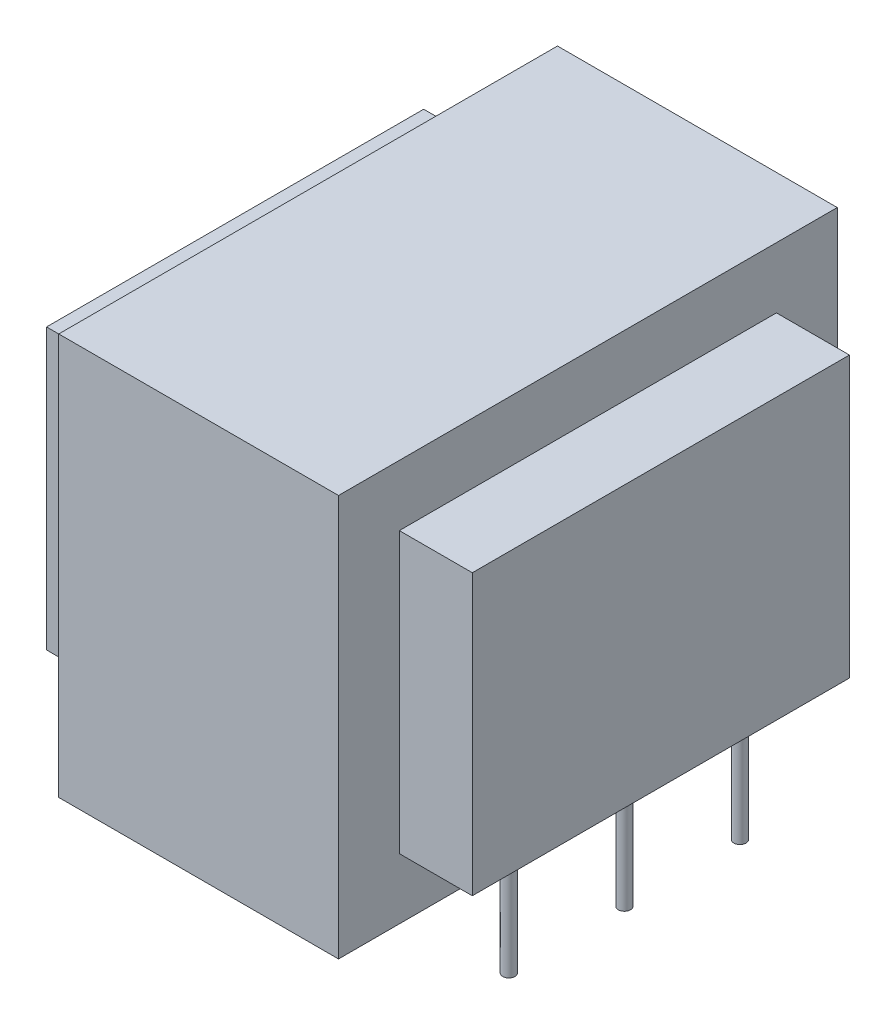
SolidWorks part; units mm, degrees
ref_plane "前视基准面" through (0, 0, 0) normal (0, 0, 1) x (1, 0, 0)
ref_plane "上视基准面" through (0, 0, 0) normal (0, 1, 0) x (1, 0, 0)
ref_plane "右视基准面" through (0, 0, 0) normal (1, 0, 0) x (0, 0, -1)
other "Configuration Table"
sketch "草图1" plane through (0, 0, 0) normal (0, 1, 0) x (1, 0, 0)
  line L1 (0, 0) -> (35, 0)
  line L2 (0, 0) -> (0, 41)
  line L3 (0, 41) -> (35, 41)
  line L4 (35, 0) -> (35, 41)
  dimension "D1" = 41
  dimension "D2" = 35
extrude "凸台-拉伸1" add sketch "草图1" along normal blind 33
sketch "草图3" plane through (35, 0, 0) normal (1, 0, 0) x (0, 0, -1)
  line L0 (5, 28) -> (5, 5)
  line L1 (5, 5) -> (36, 5)
  line L2 (36, 5) -> (36, 28)
  line L3 (36, 28) -> (5, 28)
  line L4 (20.5, 33) -> (20.5, -1.4609) construction
  line L5 (0, 33) -> (41, 33) construction
  line L6 (0, 16.5) -> (46.9727, 16.5) construction
  line L7 (0, 33) -> (0, 0) construction
  line L8 (0, 0) -> (41, 0) construction
  line L9 (41, 33) -> (41, 0) construction
  line L10 (0, 0) -> (41, 0)
  line L11 (41, 33) -> (41, 0)
  line L12 (0, 33) -> (41, 33)
  line L13 (0, 33) -> (0, 0)
  line M7 (0, 0) -> (41, 0)
  line M8 (41, 0) -> (41, 33)
  line M9 (41, 33) -> (0, 33)
  line M10 (0, 33) -> (0, 0)
  dimension "D1" = 5
  dimension "D2" = 5
extrude "切除-拉伸1" cut sketch "草图3" against normal blind 6 contours L3 L2 L1 L0 M10 M7 M8 M9
ref_plane "基准面2" through (17.5, 0, 0) normal (1, 0, 0) x (0, 0, -1)
mirror "镜向9" about plane through (17.5, 0, 0) normal (1, 0, 0) of "切除-拉伸1"
sketch "草图2" plane through (0, 5, 0) normal (0, -1, 0) x (1, 0, 0)
  line L0 (17.5, 0) -> (17.5, -46.0141) construction
  line L1 (6, 0) -> (29, 0) construction
  line L2 (0, -20.5) -> (44.987, -20.5) construction
  line L3 (0, -41) -> (0, 0) construction
  circle A0 centre (3, -11) radius 0.5
  circle A1 centre (3, -30) radius 0.5
  circle A2 centre (32, -30) radius 0.5
  circle A3 centre (32, -11) radius 0.5
  circle A4 centre (32, -20.5) radius 0.5
  dimension "D1" = 1
  dimension "D2" = 19
  dimension "D3" = 29
extrude "凸台-拉伸2" add sketch "草图2" along normal blind 10
